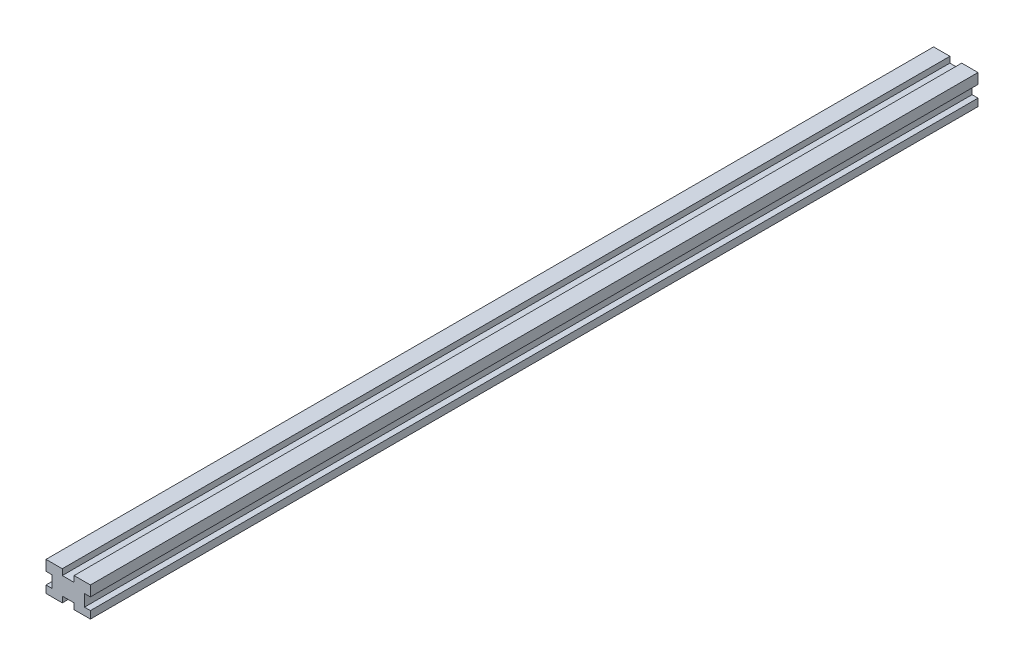
SolidWorks part; units mm, degrees
ref_plane "Front Plane" through (0, 0, 0) normal (0, 0, 1) x (1, 0, 0)
ref_plane "Top Plane" through (0, 0, 0) normal (0, 1, 0) x (1, 0, 0)
ref_plane "Right Plane" through (0, 0, 0) normal (1, 0, 0) x (0, 0, -1)
sketch "Sketch2" plane through (0, 0, 0) normal (0, 0, 1) x (1, 0, 0)
  line L1 (-7.5, -5) -> (7.5, -5)
  line L2 (-7.5, -5) -> (-7.5, 5)
  line L3 (-7.5, 5) -> (7.5, 5)
  line L4 (7.5, -5) -> (7.5, 5)
  line L5 (-7.5, -5) -> (7.5, 5) construction
  line L6 (-7.5, 5) -> (7.5, -5) construction
  point P0 (0, 0)
  dimension "D1" = 7.5
  dimension "D2" = 10
extrude "Boss-Extrude2" add sketch "Sketch2" along normal blind 300
sketch "Sketch5" plane through (0, 0, 300) normal (0, 0, 1) x (1, 0, 0)
  line L0 (7.5, 5) -> (-7.5, 5) construction
  line L1 (-2, 5) -> (2, 5)
  line L2 (-2, 5) -> (-2, 3)
  line L3 (-2, 3) -> (2, 3)
  line L4 (2, 5) -> (2, 3)
  line L5 (7.5, -5) -> (7.5, 5) construction
  line L6 (7.5, 1.5) -> (5.5, 1.5)
  line L7 (7.5, 1.5) -> (7.5, -2.5)
  line L8 (7.5, -2.5) -> (5.5, -2.5)
  line L9 (5.5, 1.5) -> (5.5, -2.5)
  line L10 (-7.5, -5) -> (7.5, -5) construction
  line L11 (2, -5) -> (-2, -5)
  line L12 (2, -5) -> (2, -3)
  line L13 (2, -3) -> (-2, -3)
  line L14 (-2, -5) -> (-2, -3)
  line L15 (-7.5, 5) -> (-7.5, -5) construction
  line L16 (-7.5, -2.5) -> (-5.5, -2.5)
  line L17 (-7.5, -2.5) -> (-7.5, 1.5)
  line L18 (-7.5, 1.5) -> (-5.5, 1.5)
  line L19 (-5.5, -2.5) -> (-5.5, 1.5)
  dimension "D1" = 4
  dimension "D2" = 2
  dimension "D3" = 5.5
  dimension "D4" = 4
  dimension "D5" = 2
  dimension "D6" = 3.5
  dimension "D7" = 4
  dimension "D8" = 2
  dimension "D9" = 5.5
  dimension "D10" = 4
  dimension "D11" = 2
  dimension "D12" = 3.5
extrude "Cut-Extrude1" cut sketch "Sketch5" against normal through all
